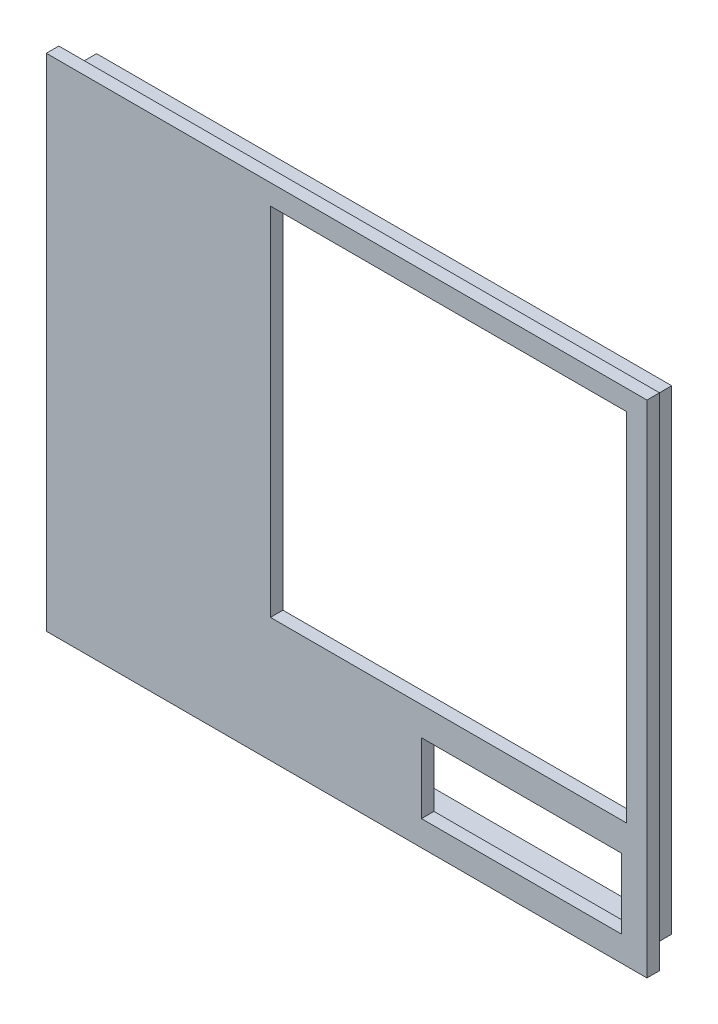
SolidWorks part; units mm, degrees
ref_plane "Front Plane" through (0, 0, 0) normal (0, 0, 1) x (1, 0, 0)
ref_plane "Top Plane" through (0, 0, 0) normal (0, 1, 0) x (1, 0, 0)
ref_plane "Right Plane" through (0, 0, 0) normal (1, 0, 0) x (0, 0, -1)
sketch "Sketch2" plane through (0, 0, 0) normal (0, 0, 1) x (1, 0, 0)
  line L1 (-60, -50) -> (60, -50)
  line L2 (-60, -50) -> (-60, 50)
  line L3 (-60, 50) -> (60, 50)
  line L4 (60, -50) -> (60, 50)
  line L5 (-60, -50) -> (60, 50) construction
  line L6 (-60, 50) -> (60, -50) construction
  point P0 (0, 0)
  dimension "D1" = 100
  dimension "D2" = 120
extrude "Boss-Extrude1" add sketch "Sketch2" along normal blind 2.5
sketch "Sketch3" plane through (0, 0, 0) normal (0, 0, -1) x (-1, 0, 0)
  line L0 (0, 0) -> (0, 50) construction
  line L1 (-60, 50) -> (60, 50) construction
  line L2 (0, 50) -> (60, 50) construction
  line L3 (60, 50) -> (60, 47.45) construction
  line L4 (60, 50) -> (60, -50) construction
  line L5 (60, 47.45) -> (57.45, 47.45) construction
  line L6 (57.45, 47.45) -> (55.95, 47.45) construction
  line L7 (-57.45, -47.45) -> (57.45, -47.45)
  line L8 (-57.45, -47.45) -> (-57.45, 47.45)
  line L9 (-57.45, 47.45) -> (57.45, 47.45)
  line L10 (57.45, -47.45) -> (57.45, 47.45)
  line L11 (55.95, 47.45) -> (55.95, 45.95)
  line L13 (-55.95, -45.95) -> (55.95, -45.95)
  line L14 (-55.95, -45.95) -> (-55.95, 45.95)
  line L15 (-55.95, 45.95) -> (55.95, 45.95)
  line L16 (55.95, -45.95) -> (55.95, 45.95)
  dimension "D1" = 2.55
  dimension "D2" = 2.55
  dimension "D3" = 1.5
  dimension "D4" = 1.5
extrude "Boss-Extrude2" add sketch "Sketch3" along normal blind 5 contours L8 L7 L10 L9 | L14 L13 L16 L15
sketch "Sketch4" plane through (0, 0, 0) normal (0, 0, -1) x (-1, 0, 0)
  line L0 (-55.95, -45.95) -> (-54.95, -45.95) construction
  line L1 (-55.95, 45.95) -> (15.22, 45.95)
  line L2 (-55.95, 45.95) -> (-55.95, -25.22)
  line L3 (-55.95, -25.22) -> (15.22, -25.22)
  line L4 (15.22, 45.95) -> (15.22, -25.22)
  line L9 (-55.95, -45.95) -> (55.95, -45.95) construction
  line L10 (-54.95, -45.95) -> (-54.95, -44.95) construction
  line L12 (-54.95, -44.95) -> (-14.95, -44.95)
  line L13 (-54.95, -44.95) -> (-54.95, -30.95)
  line L14 (-54.95, -30.95) -> (-14.95, -30.95)
  line L15 (-14.95, -44.95) -> (-14.95, -30.95)
  dimension "D1" = 71.17
  dimension "D2" = 71.17
  dimension "D3" = 1
  dimension "D4" = 1
  dimension "D5" = 40
  dimension "D6" = 14
extrude "Cut-Extrude1" cut sketch "Sketch4" against normal up to surface (2.5 mm away) up to face at (0, 0, 2.5)
